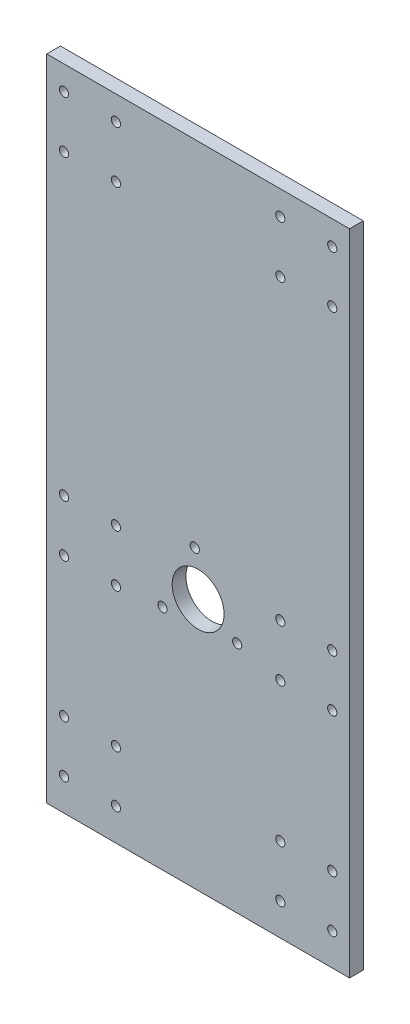
SolidWorks part; units mm, degrees
ref_plane "Front Plane" through (0, 0, 0) normal (0, 0, 1) x (1, 0, 0)
ref_plane "Top Plane" through (0, 0, 0) normal (0, 1, 0) x (1, 0, 0)
ref_plane "Right Plane" through (0, 0, 0) normal (1, 0, 0) x (0, 0, -1)
sketch "Sketch1" plane through (0, 0, 0) normal (0, 0, 1) x (1, 0, 0)
  line L0 (0, 150) -> (0, -150) construction
  line L1 (-70, -150) -> (70, -150)
  line L2 (-70, -150) -> (-70, 150)
  line L3 (-70, 150) -> (70, 150)
  line L4 (70, -150) -> (70, 150)
  line L5 (-70, -150) -> (70, 150) construction
  line L6 (-70, 150) -> (70, -150) construction
  line L7 (-70, 0) -> (70, 0) construction
  line L8 (-70, 146.825) -> (0, 146.825) construction
  line L9 (-50, 142.1136) -> (-50, 118.9658) construction
  line L12 (-63.1537, 126.825) -> (-35.7543, 126.825) construction
  line L13 (-70, -74) -> (74.7966, -74) construction
  line L15 (-70, 46) -> (70, 46) construction
  line L16 (-70, -58) -> (70, -58) construction
  line L18 (-70, -79) -> (70, -79) construction
  circle A9 centre (-62, 138.825) radius 2.125
  circle A11 centre (-38, 138.825) radius 2.125
  circle A12 centre (-38, 114.825) radius 2.125
  circle A13 centre (-62, 114.825) radius 2.125
  circle A14 centre (38, 114.825) radius 2.125
  circle A15 centre (62, 114.825) radius 2.125
  circle A16 centre (38, 138.825) radius 2.125
  circle A17 centre (62, 138.825) radius 2.125
  circle A26 centre (62, -46.825) radius 2.125
  circle A27 centre (38, -46.825) radius 2.125
  circle A28 centre (62, -22.825) radius 2.125
  circle A29 centre (38, -22.825) radius 2.125
  circle A30 centre (-62, -22.825) radius 2.125
  circle A31 centre (-38, -22.825) radius 2.125
  circle A32 centre (-38, -46.825) radius 2.125
  circle A33 centre (-62, -46.825) radius 2.125
  circle A34 centre (-62, -111.175) radius 2.125
  circle A35 centre (-38, -111.175) radius 2.125
  circle A36 centre (-38, -135.175) radius 2.125
  circle A37 centre (-62, -135.175) radius 2.125
  circle A38 centre (38, -135.175) radius 2.125
  circle A39 centre (62, -135.175) radius 2.125
  circle A40 centre (38, -111.175) radius 2.125
  circle A41 centre (62, -111.175) radius 2.125
  point P0 (0, 0)
  dimension "D4" = 4.25
  dimension "D6" = 8
  dimension "D7" = 12
  dimension "D9" = 224
  dimension "D11" = 11.175
  dimension "D12" = 5
  dimension "D1" = 300
  dimension "D2" = 140
  dimension "D3" = 3.175
  dimension "D5" = 8
  dimension "D8" = 12
  dimension "D10" = 120
extrude "Boss-Extrude1" add sketch "Sketch1" along normal blind 6.35
sketch "Sketch2" plane through (0, 0, 6.35) normal (0, 0, 1) x (1, 0, 0)
  line L0 (-70, -248.35) -> (70, -248.35) construction
  line L1 (-70, 150) -> (-70, -150) construction
  line L2 (70, -150) -> (70, 150) construction
  line L3 (70, 150) -> (-70, 150) construction
  line L4 (-70, -33.35) -> (70, -33.35) construction
  circle A0 centre (0, -33.35) radius 12
  circle A1 centre (-1.5653, -13.4114) radius 2.125
  circle A2 centre (18.05, -41.9637) radius 2.125
  circle A3 centre (-16.4847, -44.6749) radius 2.125
  point P20 (0, 0)
  point P22 (0, -33.35)
  dimension "D3" = 4.25
  dimension "D6" = 24
  dimension "D1" = 398.35
  dimension "D2" = 215
  dimension "D4" = 20
  dimension "D5" = 3
extrude "Cut-Extrude1" cut sketch "Sketch2" against normal through all
